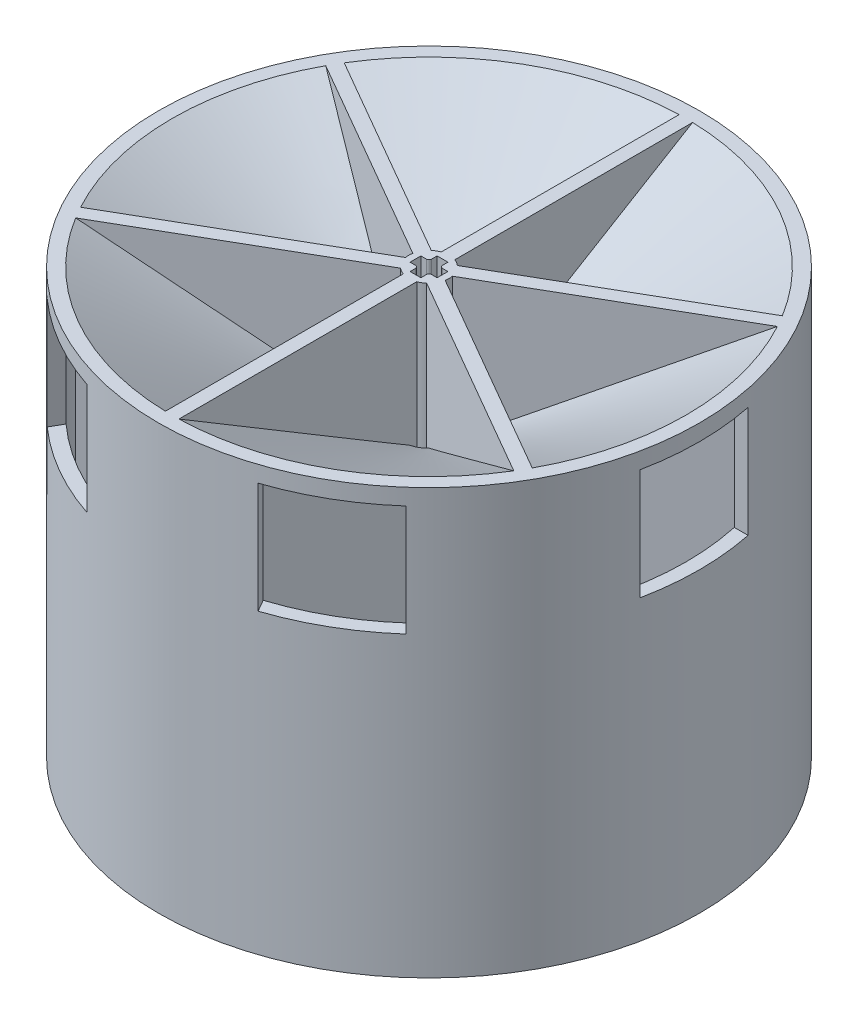
SolidWorks part; units mm, degrees
ref_plane "Front Plane" through (0, 0, 0) normal (0, 0, 1) x (1, 0, 0)
ref_plane "Top Plane" through (0, 0, 0) normal (0, 1, 0) x (1, 0, 0)
ref_plane "Right Plane" through (0, 0, 0) normal (1, 0, 0) x (0, 0, -1)
sketch "Sketch1" plane through (0, 0, 0) normal (0, 1, 0) x (1, 0, 0)
  line L12 (-40.4974, -24.8246) -> (-2.4139, -2.837)
  line L13 (1.25, -47.4841) -> (1.25, -3.509)
  line L14 (-1.25, -47.4841) -> (-1.25, -3.509)
  line L15 (1.25, 47.4841) -> (0.1464, 5.5614) construction
  line L16 (-41.7474, -22.6595) -> (-3.6639, -0.672)
  line L17 (-41.7474, 22.6595) -> (-3.6639, 0.672)
  line L18 (-40.4974, 24.8246) -> (-2.4139, 2.837)
  line L19 (-1.25, 47.4841) -> (-1.25, 3.509)
  line L20 (1.25, 47.4841) -> (1.25, 3.509)
  line L21 (40.4974, 24.8246) -> (2.4139, 2.837)
  line L22 (41.7474, 22.6595) -> (3.6639, 0.672)
  line L23 (41.7474, -22.6595) -> (3.6639, -0.672)
  line L24 (40.4974, -24.8246) -> (2.4139, -2.837)
  line L40 (-1, 2.5) -> (1, 2.5)
  line L43 (2.5, -1) -> (2.5, 1)
  line L44 (1, 2.5) -> (1, 1.5)
  line L45 (1.5, 1) -> (2.5, 1)
  line L46 (1.5, -1) -> (2.5, -1)
  line L48 (-1, -2.5) -> (1, -2.5)
  line L49 (1, -2.5) -> (1, -1.5)
  line L50 (-2.5, -1) -> (-2.5, 1)
  line L51 (-1.5, 1) -> (-2.5, 1)
  line L52 (-1, 2.5) -> (-1, 1.5)
  line L53 (-1.5, -1) -> (-2.5, -1)
  line L54 (-1, -2.5) -> (-1, -1.5)
  circle A4 centre (0, 0) radius 50.0005
  arc A5 (1.25, -47.4841) -> (40.4974, -24.8246) centre (0, 0) ccw
  arc A6 (41.7474, -22.6595) -> (41.7474, 22.6595) centre (0, 0) ccw
  arc A7 (-40.4974, -24.8246) -> (-1.25, -47.4841) centre (0, 0) ccw
  arc A8 (-1.25, 47.4841) -> (-40.4974, 24.8246) centre (0, 0) ccw
  arc A9 (40.4974, 24.8246) -> (1.25, 47.4841) centre (0, 0) ccw
  arc A10 (-41.7474, 22.6595) -> (-41.7474, -22.6595) centre (0, 0) ccw
  arc A11 (-2.4139, -2.837) -> (-1.25, -3.509) centre (0, 0) ccw
  arc A12 (-3.6639, 0.672) -> (-3.6639, -0.672) centre (0, 0) ccw
  arc A13 (-1.25, 3.509) -> (-2.4139, 2.837) centre (0, 0) ccw
  arc A14 (0.098, 3.7237) -> (-0.098, 3.7237) centre (0, 0) ccw
  arc A15 (2.4139, 2.837) -> (1.25, 3.509) centre (0, 0) ccw
  arc A16 (3.6639, -0.672) -> (3.6639, 0.672) centre (0, 0) ccw
  arc A17 (1.25, -3.509) -> (2.4139, -2.837) centre (0, 0) ccw
  arc A18 (-1.5, 1) -> (-1, 1.5) centre (-1.5, 1.5) ccw
  arc A19 (1.5, 1) -> (1, 1.5) centre (1.5, 1.5) cw
  arc A20 (1.5, -1) -> (1, -1.5) centre (1.5, -1.5) ccw
  arc A21 (-1, -1.5) -> (-1.5, -1) centre (-1.5, -1.5) ccw
  point P45 (0, 0)
  dimension "D1" = 0.5
extrude "Boss-Extrude1" add sketch "Sketch1" against normal blind 50
sketch "Sketch3" plane through (0, 0, 0) normal (0, 0, 1) x (1, 0, 0)
  line L0 (47.5005, 0) -> (47.5005, 25.5845)
  line L1 (50.0005, 0) -> (50.0005, 30)
  line L2 (50.0005, 30) -> (5.0829, 3.0497)
  line L3 (47.5005, 25.5845) -> (4.8592, 0)
  line L4 (1.1203, 0) -> (4.8592, 0)
  line L5 (50.0005, 0) -> (47.5005, 0)
  line L7 (50.0005, 30) -> (0, 0) construction
  line L8 (47.5005, 25.5845) -> (1.2862, -2.1437) construction
  line L10 (1.1203, 0) -> (5.0829, 3.0497)
  line L11 (0, 10.4372) -> (0, 41.0476)
  dimension "D1" = 2.5
revolve "Revolve1" add sketch "Sketch3" angle 360 about L11
sketch "Sketch4" plane through (0, 0, 0) normal (0, -1, 0) x (1, 0, 0)
  line L0 (-40.4974, -24.8246) -> (-2.4139, -2.837)
  line L1 (1.25, -47.4841) -> (1.25, -3.509)
  line L2 (-1.25, -47.4841) -> (-1.25, -3.509)
  line L3 (1.25, 47.4841) -> (0.1464, 5.5614) construction
  line L4 (-41.7474, -22.6595) -> (-3.6639, -0.672)
  line L5 (-41.7474, 22.6595) -> (-3.6639, 0.672)
  line L6 (-40.4974, 24.8246) -> (-2.4139, 2.837)
  line L7 (-1.25, 47.4841) -> (-1.25, 3.509)
  line L8 (1.25, 47.4841) -> (1.25, 3.509)
  line L9 (40.4974, 24.8246) -> (2.4139, 2.837)
  line L10 (41.7474, 22.6595) -> (3.6639, 0.672)
  line L11 (41.7474, -22.6595) -> (3.6639, -0.672)
  line L12 (40.4974, -24.8246) -> (2.4139, -2.837)
  line L13 (-1, 2.5) -> (1, 2.5)
  line L14 (2.5, -1) -> (2.5, 1)
  line L15 (1, 2.5) -> (1, 1.5)
  line L16 (1.5, 1) -> (2.5, 1)
  line L17 (1.5, -1) -> (2.5, -1)
  line L18 (-1, -2.5) -> (1, -2.5)
  line L19 (1, -2.5) -> (1, -1.5)
  line L20 (-2.5, -1) -> (-2.5, 1)
  line L21 (-1.5, 1) -> (-2.5, 1)
  line L22 (-1, 2.5) -> (-1, 1.5)
  line L23 (-1.5, -1) -> (-2.5, -1)
  line L24 (-1, -2.5) -> (-1, -1.5)
  circle A0 centre (0, 0) radius 50.0005
  arc A1 (1.25, -47.4841) -> (40.4974, -24.8246) centre (0, 0) ccw
  arc A2 (41.7474, -22.6595) -> (41.7474, 22.6595) centre (0, 0) ccw
  arc A3 (-40.4974, -24.8246) -> (-1.25, -47.4841) centre (0, 0) ccw
  arc A4 (-1.25, 47.4841) -> (-40.4974, 24.8246) centre (0, 0) ccw
  arc A5 (40.4974, 24.8246) -> (1.25, 47.4841) centre (0, 0) ccw
  arc A6 (-41.7474, 22.6595) -> (-41.7474, -22.6595) centre (0, 0) ccw
  arc A7 (-2.4139, -2.837) -> (-1.25, -3.509) centre (0, 0) ccw
  arc A8 (-3.6639, 0.672) -> (-3.6639, -0.672) centre (0, 0) ccw
  arc A9 (-1.25, 3.509) -> (-2.4139, 2.837) centre (0, 0) ccw
  arc A10 (0.098, 3.7237) -> (-0.098, 3.7237) centre (0, 0) ccw
  arc A11 (2.4139, 2.837) -> (1.25, 3.509) centre (0, 0) ccw
  arc A12 (3.6639, -0.672) -> (3.6639, 0.672) centre (0, 0) ccw
  arc A13 (1.25, -3.509) -> (2.4139, -2.837) centre (0, 0) ccw
  arc A14 (-1.5, 1) -> (-1, 1.5) centre (-1.5, 1.5) ccw
  arc A15 (1.5, 1) -> (1, 1.5) centre (1.5, 1.5) cw
  arc A16 (1.5, -1) -> (1, -1.5) centre (1.5, -1.5) ccw
  arc A17 (-1, -1.5) -> (-1.5, -1) centre (-1.5, -1.5) ccw
  point P42 (0, 0)
  dimension "D1" = 0.5
extrude "Boss-Extrude2" add sketch "Sketch4" against normal blind 30
sketch "Sketch5" plane through (0, 30, 0) normal (0, 1, 0) x (1, 0, 0)
  line L0 (14.5577, -45.2147) -> (15.8349, -47.4269)
  line L1 (46.436, -10) -> (48.9903, -10)
  line L2 (46.436, 10) -> (48.9903, 10)
  line L3 (31.8782, -35.2147) -> (33.1554, -37.4269)
  line L4 (-31.8782, -35.2147) -> (-33.1554, -37.4269)
  line L5 (-14.5577, -45.2147) -> (-15.8349, -47.4269)
  line L6 (-46.436, 10) -> (-48.9903, 10)
  line L7 (-46.436, -10) -> (-48.9903, -10)
  line L8 (-14.5577, 45.2147) -> (-15.8349, 47.4269)
  line L9 (-31.8782, 35.2147) -> (-33.1554, 37.4269)
  line L10 (31.8782, 35.2147) -> (33.1554, 37.4269)
  line L11 (14.5577, 45.2147) -> (15.8349, 47.4269)
  arc A1 (48.9903, -10) -> (48.9903, 10) centre (0, 0) ccw
  arc A2 (46.436, -10) -> (46.436, 10) centre (0, 0) ccw
  arc A3 (15.8349, -47.4269) -> (33.1554, -37.4269) centre (0, 0) ccw
  arc A4 (14.5577, -45.2147) -> (31.8782, -35.2147) centre (0, 0) ccw
  arc A5 (-33.1554, -37.4269) -> (-15.8349, -47.4269) centre (0, 0) ccw
  arc A6 (-31.8782, -35.2147) -> (-14.5577, -45.2147) centre (0, 0) ccw
  arc A7 (-48.9903, 10) -> (-48.9903, -10) centre (0, 0) ccw
  arc A8 (-46.436, 10) -> (-46.436, -10) centre (0, 0) ccw
  arc A9 (-15.8349, 47.4269) -> (-33.1554, 37.4269) centre (0, 0) ccw
  arc A10 (-14.5577, 45.2147) -> (-31.8782, 35.2147) centre (0, 0) ccw
  arc A11 (33.1554, 37.4269) -> (15.8349, 47.4269) centre (0, 0) ccw
  arc A12 (31.8782, 35.2147) -> (14.5577, 45.2147) centre (0, 0) ccw
  point P29 (0, 0)
  dimension "D1" = 6
sketch "Sketch7" plane through (0, 30, 0) normal (0, 1, 0) x (1, 0, 0)
  line L0 (14.5577, -45.2147) -> (15.8349, -47.4269)
  line L1 (46.436, -10) -> (48.9903, -10)
  line L2 (46.436, 10) -> (48.9903, 10)
  line L3 (31.8782, -35.2147) -> (33.1554, -37.4269)
  line L4 (-31.8782, -35.2147) -> (-33.1554, -37.4269)
  line L5 (-14.5577, -45.2147) -> (-15.8349, -47.4269)
  line L6 (-46.436, 10) -> (-48.9903, 10)
  line L7 (-46.436, -10) -> (-48.9903, -10)
  line L8 (-14.5577, 45.2147) -> (-15.8349, 47.4269)
  line L9 (-31.8782, 35.2147) -> (-33.1554, 37.4269)
  line L10 (31.8782, 35.2147) -> (33.1554, 37.4269)
  line L11 (14.5577, 45.2147) -> (15.8349, 47.4269)
  arc A0 (48.9903, -10) -> (48.9903, 10) centre (0, 0) ccw
  arc A1 (46.436, -10) -> (46.436, 10) centre (0, 0) ccw
  arc A2 (15.8349, -47.4269) -> (33.1554, -37.4269) centre (0, 0) ccw
  arc A3 (14.5577, -45.2147) -> (31.8782, -35.2147) centre (0, 0) ccw
  arc A4 (-33.1554, -37.4269) -> (-15.8349, -47.4269) centre (0, 0) ccw
  arc A5 (-31.8782, -35.2147) -> (-14.5577, -45.2147) centre (0, 0) ccw
  arc A6 (-48.9903, 10) -> (-48.9903, -10) centre (0, 0) ccw
  arc A7 (-46.436, 10) -> (-46.436, -10) centre (0, 0) ccw
  arc A8 (-15.8349, 47.4269) -> (-33.1554, 37.4269) centre (0, 0) ccw
  arc A9 (-14.5577, 45.2147) -> (-31.8782, 35.2147) centre (0, 0) ccw
  arc A10 (33.1554, 37.4269) -> (15.8349, 47.4269) centre (0, 0) ccw
  arc A11 (31.8782, 35.2147) -> (14.5577, 45.2147) centre (0, 0) ccw
  point P25 (0, 0)
extrude "Cut-Extrude2" cut sketch "Sketch7" against normal blind 25
sketch "Sketch9" plane through (0, 30, 0) normal (0, 1, 0) x (1, 0, 0)
  circle A0 centre (0, 0) radius 50.0005
extrude "Cut-Extrude3" cut sketch "Sketch9" against normal blind 1.5
sketch "Sketch11" plane through (0, 28.5, 0) normal (0, 1, 0) x (1, 0, 0)
  line L0 (14.5577, -45.2147) -> (15.8349, -47.4269)
  line L1 (46.436, -10) -> (48.9903, -10)
  line L2 (46.436, 10) -> (48.9903, 10)
  line L3 (31.8782, -35.2147) -> (33.1554, -37.4269)
  line L4 (-31.8782, -35.2147) -> (-33.1554, -37.4269)
  line L5 (-14.5577, -45.2147) -> (-15.8349, -47.4269)
  line L6 (-46.436, 10) -> (-48.9903, 10)
  line L7 (-46.436, -10) -> (-48.9903, -10)
  line L8 (-14.5577, 45.2147) -> (-15.8349, 47.4269)
  line L9 (-31.8782, 35.2147) -> (-33.1554, 37.4269)
  line L10 (31.8782, 35.2147) -> (33.1554, 37.4269)
  line L11 (14.5577, 45.2147) -> (15.8349, 47.4269)
  arc A0 (48.9903, -10) -> (48.9903, 10) centre (0, 0) ccw
  arc A1 (46.436, -10) -> (46.436, 10) centre (0, 0) ccw
  arc A2 (15.8349, -47.4269) -> (33.1554, -37.4269) centre (0, 0) ccw
  arc A3 (14.5577, -45.2147) -> (31.8782, -35.2147) centre (0, 0) ccw
  arc A4 (-33.1554, -37.4269) -> (-15.8349, -47.4269) centre (0, 0) ccw
  arc A5 (-31.8782, -35.2147) -> (-14.5577, -45.2147) centre (0, 0) ccw
  arc A6 (-48.9903, 10) -> (-48.9903, -10) centre (0, 0) ccw
  arc A7 (-46.436, 10) -> (-46.436, -10) centre (0, 0) ccw
  arc A8 (-15.8349, 47.4269) -> (-33.1554, 37.4269) centre (0, 0) ccw
  arc A9 (-14.5577, 45.2147) -> (-31.8782, 35.2147) centre (0, 0) ccw
  arc A10 (33.1554, 37.4269) -> (15.8349, 47.4269) centre (0, 0) ccw
  arc A11 (31.8782, 35.2147) -> (14.5577, 45.2147) centre (0, 0) ccw
  point P25 (0, 0)
extrude "Boss-Extrude3" add sketch "Sketch11" against normal blind 3
sketch "Sketch12" plane through (0, 28.5, 0) normal (0, 1, 0) x (1, 0, 0)
  line L0 (-1, 2.5) -> (1, 2.5)
  line L4 (2.5, 1) -> (2.5, -1)
  line L8 (1, -2.5) -> (-1, -2.5)
  line L9 (-1, -2.5) -> (-1, -1.5)
  line L10 (-1.5, -1) -> (-2.5, -1)
  line L11 (-2.5, -1) -> (-2.5, 1)
  line L15 (-2.5, 1) -> (-1.5, 1)
  line L16 (-1, 1.5) -> (-1, 2.5)
  line L17 (1, 2.5) -> (1, 1.5)
  line L18 (1.5, 1) -> (2.5, 1)
  line L19 (1, -2.5) -> (1, -1.5)
  line L20 (1.5, -1) -> (2.5, -1)
  arc A0 (-1, -1.5) -> (-1.5, -1) centre (-1.5, -1.5) ccw
  arc A1 (1, -1.5) -> (1.5, -1) centre (1.5, -1.5) cw
  arc A2 (1.5, 1) -> (1, 1.5) centre (1.5, 1.5) cw
  arc A3 (-1, 1.5) -> (-1.5, 1) centre (-1.5, 1.5) cw
  dimension "D1" = 0.5
  dimension "D2" = 0.5
extrude "Cut-Extrude4" cut sketch "Sketch12" against normal blind 84
